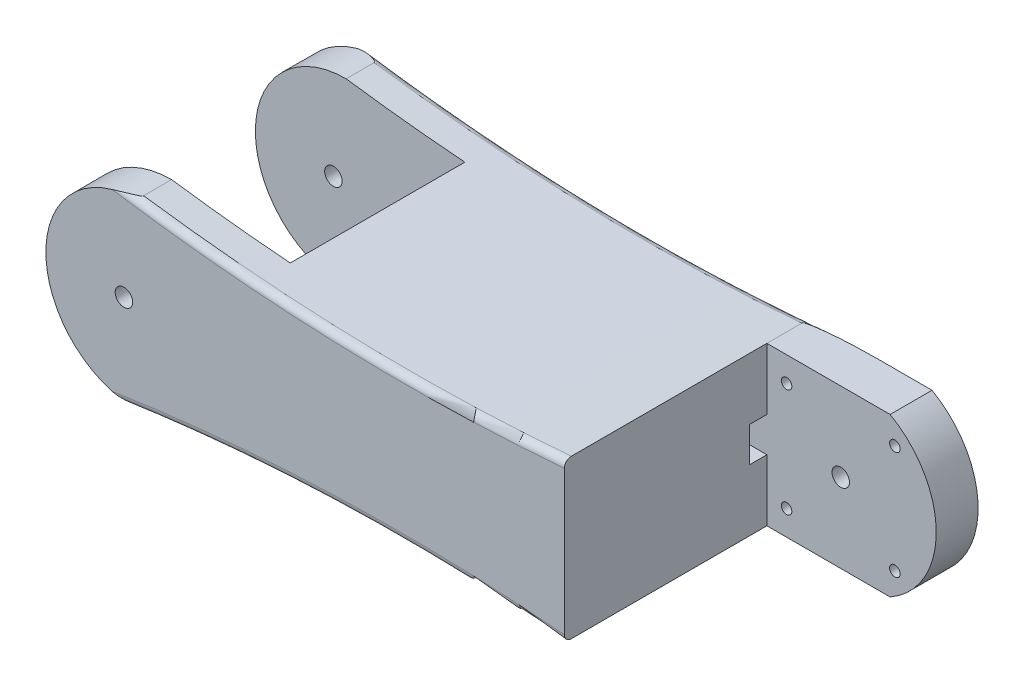
SolidWorks part; units mm, degrees
material "ABS"
ref_plane "Front Plane" through (0, 0, 0) normal (0, 0, 1) x (1, 0, 0)
ref_plane "Top Plane" through (0, 0, 0) normal (0, 1, 0) x (1, 0, 0)
ref_plane "Right Plane" through (0, 0, 0) normal (1, 0, 0) x (0, 0, -1)
sketch "Sketch1" plane through (0, 0, 0) normal (0, 1, 0) x (1, 0, 0)
  line L1 (-100, -35) -> (100, -35)
  line L2 (-100, -35) -> (-100, 35)
  line L3 (-100, 35) -> (100, 35)
  line L4 (100, -35) -> (100, 35)
  line L5 (-100, -35) -> (100, 35) construction
  line L6 (-100, 35) -> (100, -35) construction
  point P0 (0, 0)
  dimension "D1" = 200
  dimension "D2" = 70
extrude "Boss-Extrude1" add sketch "Sketch1" along normal blind 55
sketch "Sketch3" plane through (0, 0, 0) normal (0, 0, 1) x (1, 0, 0)
  line L1 (100, 55) -> (50, 55)
  line L5 (0, 0) -> (0, 55) construction
  line L6 (-100, 55) -> (100, 55) construction
  line L8 (100, 55) -> (100, 0)
  line L13 (50, 55) -> (50, 0)
  line L14 (-100, 0) -> (100, 0) construction
  line L15 (50, 0) -> (100, 0)
  line L19 (100, 55) -> (100, 0) construction
  dimension "D1" = 50
  dimension "D2" = 0
extrude "Cut-Extrude1" cut sketch "Sketch3" against normal mid plane 46
sketch "Sketch4" plane through (0, 0, 35) normal (0, 0, 1) x (1, 0, 0)
  line L1 (-100, 55) -> (100, 55) construction
  line L2 (0, 0) -> (0, 55) construction
  line L3 (-72.5, 27.5) -> (72.5, 27.5) construction
  arc A0 (-72.5, 53.5) -> (-72.5, 1.5) centre (-72.5, 27.5) ccw
  arc A1 (77.0631, 53.0965) -> (77.0631, 1.9035) centre (72.5, 27.5) cw
  arc A2 (77.0631, 53.0965) -> (-72.5, 53.5) centre (3.7517, 598.1886) cw
  arc A3 (77.0631, 1.9035) -> (-72.5, 1.5) centre (3.7517, -543.1886) ccw
  point P1 (0, 0)
  point P2 (0, 0)
  point P3 (-72.5, 45.2808)
  point P10 (0, 0)
  dimension "D1" = 26
  dimension "D2" = 26
  dimension "D4" = 550
extrude "Cut-Extrude2" cut sketch "Sketch4" against normal through all both and the other way through all flip side to cut
fillet "Fillet2" radius 2 4 edges at (2.2678, 48.1906, -35) (2.2678, 6.8094, -35) (2.2678, 48.1906, 35) (2.2678, 6.8094, 35)
sketch "Sketch11" plane through (0, 0, 35) normal (0, 0, 1) x (1, 0, 0)
  circle A0 centre (-76.15, 27.5) radius 2.5
  arc A2 (-79.586, 52.5158) -> (-79.586, 2.4842) centre (-72.5, 27.5) ccw construction
  point P7 (-98.5, 27.5)
  dimension "D1" = 76.15
  dimension "D2" = 5
  dimension "D3" = 0
extrude "Cut-Extrude6" cut sketch "Sketch11" against normal through all both and the other way through all
sketch "Sketch12" plane through (0, 0, 0) normal (0, 0, 1) x (1, 0, 0)
  line L1 (-144.9202, 66.422) -> (-38.5, 66.422)
  line L2 (-144.9202, 66.422) -> (-144.9202, -14.8065)
  line L3 (-144.9202, -14.8065) -> (-38.5, -14.8065)
  line L4 (-38.5, 66.422) -> (-38.5, -14.8065)
  arc A0 (-79.586, 52.5158) -> (-79.586, 2.4842) centre (-72.5, 27.5) ccw construction
  point P7 (-98.5, 27.5)
  dimension "D1" = 60
extrude "Cut-Extrude7" cut sketch "Sketch12" against normal mid plane 50
sketch "Sketch13" plane through (0, 0, 23) normal (0, 0, -1) x (-1, 0, 0)
  line L1 (-50, 4.8635) -> (-50, 50.1365)
  line L2 (-50, 4.8635) -> (-50, 50.1365)
  arc A3 (-77.0631, 53.0965) -> (-50, 50.1365) centre (-3.7517, 598.1886) ccw
  arc A4 (-77.0631, 53.0965) -> (-77.0631, 1.9035) centre (-72.5, 27.5) ccw
  arc A5 (-50, 4.8635) -> (-77.0631, 1.9035) centre (-3.7517, -543.1886) ccw
  arc A6 (-77.0631, 53.0965) -> (-50, 50.1365) centre (-3.7517, 598.1886) ccw
  arc A7 (-77.0631, 53.0965) -> (-77.0631, 1.9035) centre (-72.5, 27.5) ccw
  arc A8 (-50, 4.8635) -> (-77.0631, 1.9035) centre (-3.7517, -543.1886) ccw
  dimension "D1" = 0
extrude "Cut-Extrude8" cut sketch "Sketch13" against normal through all
sketch "Sketch14" plane through (0, 0, -23) normal (0, 0, 1) x (1, 0, 0)
  line L0 (50, 4.8635) -> (79.4425, -11.3042)
  line L1 (50, 4.8635) -> (98.5, 4.8635)
  line L3 (50, 50.1365) -> (98.5, 50.1365)
  line L4 (98.5, 4.8635) -> (98.5, 50.1365)
  line L5 (79.4425, -11.3042) -> (157.5937, 0)
  line L6 (157.5937, 0) -> (128.4629, 83.2343)
  line L7 (128.4629, 83.2343) -> (50, 50.1365)
  arc A0 (77.0631, 1.9035) -> (77.0631, 53.0965) centre (72.5, 27.5) ccw construction
  dimension "D1" = 0
extrude "Cut-Extrude9" cut sketch "Sketch14" against normal blind 50
sketch "Sketch15" plane through (0, 0, -23) normal (0, 0, 1) x (1, 0, 0)
  line L0 (50, 50.1365) -> (50, 4.8635) construction
  line L1 (71.15, 27.5) -> (71.15, 50.1365) construction
  line L2 (50, 50.1365) -> (85.2902, 50.1365) construction
  line L3 (71.15, 27.5) -> (55.6502, 42.9998) construction
  circle A0 centre (71.15, 27.5) radius 2.5
  arc A1 (85.2902, 4.8635) -> (85.2902, 50.1365) centre (72.5, 27.5) ccw construction
  circle A2 centre (55.6502, 42.9998) radius 1.5
  circle A3 centre (86.6498, 42.9998) radius 1.5
  circle A4 centre (86.6498, 12.0002) radius 1.5
  circle A5 centre (55.6502, 12.0002) radius 1.5
  point P20 (71.15, 27.5)
  dimension "D1" = 0
  dimension "D2" = 21.15
  dimension "D3" = 5
  dimension "D4" = 3
  dimension "D5" = 21.92
  dimension "D6" = 45
  dimension "D7" = 4
extrude "Cut-Extrude10" cut sketch "Sketch15" against normal blind 50
sketch "Sketch16" plane through (50, 0, 0) normal (1, 0, 0) x (0, 0, -1)
  line L0 (23, 50.1365) -> (23, 4.8635) construction
  line L1 (23, 22.5) -> (18, 22.5)
  line L2 (23, 22.5) -> (23, 32.5)
  line L3 (23, 32.5) -> (18, 32.5)
  line L4 (18, 22.5) -> (18, 32.5)
  point P4 (23, 27.5)
  point P7 (23, 27.5)
  dimension "D1" = 0
  dimension "D2" = 0
  dimension "D3" = 5
  dimension "D4" = 10
extrude "Cut-Extrude11" cut sketch "Sketch16" against normal through all
